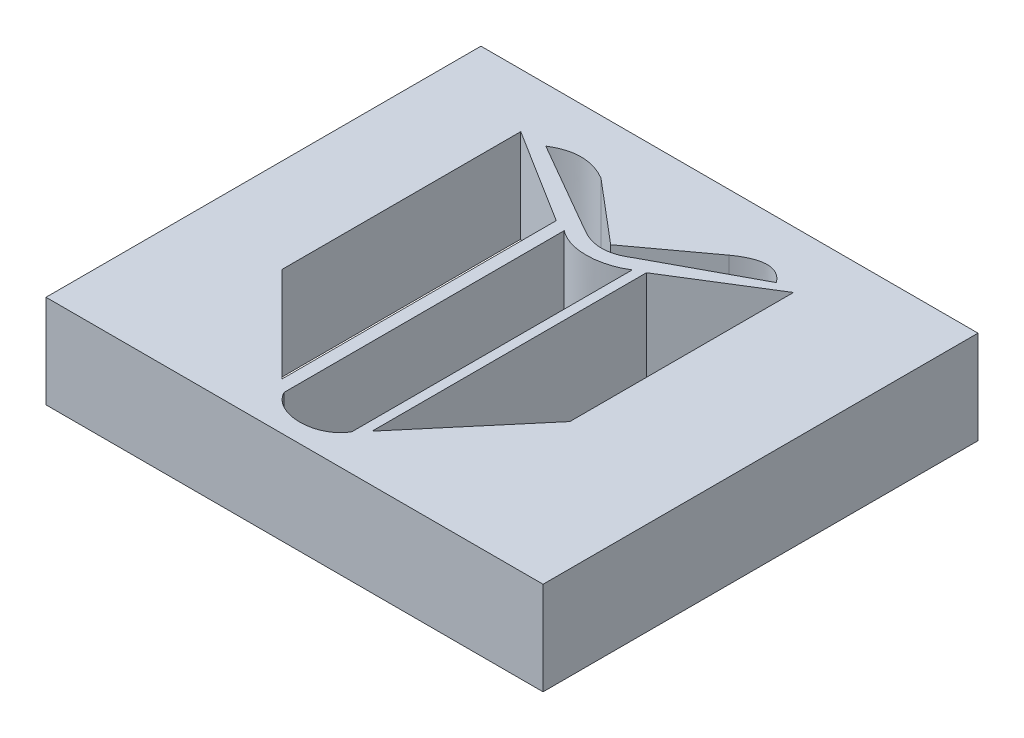
SolidWorks part; units mm, degrees
ref_plane "Front Plane" through (0, 0, 0) normal (0, 0, 1) x (1, 0, 0)
ref_plane "Top Plane" through (0, 0, 0) normal (0, 1, 0) x (1, 0, 0)
ref_plane "Right Plane" through (0, 0, 0) normal (1, 0, 0) x (0, 0, -1)
sketch "Sketch2" plane through (0, 0, 0) normal (0, 1, 0) x (1, 0, 0)
  line L1 (-42.8025, 22.3185) -> (-26.8025, 22.3185)
  line L2 (-42.8025, 22.3185) -> (-42.8025, 8.3185)
  line L3 (-42.8025, 8.3185) -> (-26.8025, 8.3185)
  line L4 (-26.8025, 22.3185) -> (-26.8025, 8.3185)
  dimension "D1" = 16
  dimension "D2" = 14
extrude "Boss-Extrude1" add sketch "Sketch2" along normal blind 3 contours L1 L4 L3 L2
sketch "Sketch4" plane through (0, 3, 0) normal (0, 1, 0) x (1, 0, 0)
  line L0 (44.0703, 264.4267) -> (385.4036, 264.4267) construction
  line L3 (122.1128, 434.8531) -> (775.4462, 434.8531) construction
  line L24 (-36.3189, 18.5161) -> (-36.3189, 9.4958)
  line L36 (-34.13, 18.5161) -> (-34.13, 9.4958)
  line L37 (-33.8221, 18.6665) -> (-33.8221, 9.8313)
  line L38 (-33.8221, 9.8313) -> (-30.9059, 13.284)
  line L39 (-30.9059, 13.284) -> (-30.9059, 20.4818)
  line L40 (-30.9059, 20.4818) -> (-33.8221, 18.6665)
  line L41 (-36.7266, 18.6665) -> (-36.7266, 9.8313)
  line L42 (-36.7266, 9.8313) -> (-39.7792, 12.8839)
  line L43 (-39.7792, 12.8839) -> (-39.7792, 20.5759)
  line L44 (-39.7792, 20.5759) -> (-36.7266, 18.6665)
  line L46 (-37.1972, 20.5759) -> (-35.1792, 18.8715)
  line L47 (-38.9724, 20.5759) -> (-36.0138, 18.8715)
  line L48 (-35.1033, 18.9273) -> (-32.9881, 20.4818)
  line L50 (-31.455, 20.4818) -> (-34.4539, 18.8715)
  line L54 (-35.1033, 18.9273) -> (-35.1792, 18.8715)
  spline S0 degree 3 poles (-36.3189, 18.5161) (-35.7096, 18.039) (-34.7645, 18.1148) (-34.13, 18.5161) knots 0 0 0 0 1 1 1 1
  spline S1 degree 3 poles (-36.3189, 9.4958) (-35.9139, 8.7209) (-34.5433, 8.741) (-34.13, 9.4958) knots 0 0 0 0 1 1 1 1
  spline S2 degree 2 poles (-36.0138, 18.8715) (-35.2239, 18.3789) (-34.4539, 18.8715) knots 0 0 0 1 1 1
  spline S3 degree 2 poles (-38.9724, 20.5759) (-38.1192, 21.1146) (-37.1972, 20.5759) knots 0 0 0 1 1 1
  spline S4 degree 2 poles (-32.9881, 20.4818) (-31.9964, 21.1944) (-31.455, 20.4818) knots 0 0 0 1 1 1
extrude "Cut-Extrude1" cut sketch "Sketch4" against normal blind 3
